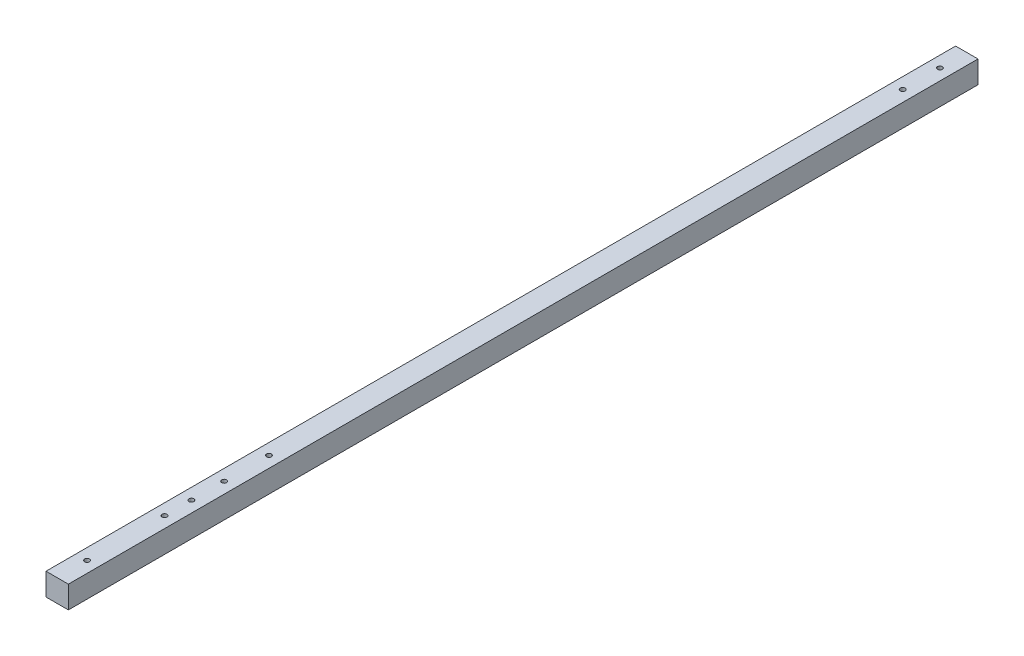
SolidWorks part; units mm, degrees
ref_plane "前视基准面" through (0, 0, 0) normal (0, 0, 1) x (1, 0, 0)
ref_plane "上视基准面" through (0, 0, 0) normal (0, 1, 0) x (1, 0, 0)
ref_plane "右视基准面" through (0, 0, 0) normal (1, 0, 0) x (0, 0, -1)
sketch "草图1" plane through (0, 0, 0) normal (0, 0, 1) x (1, 0, 0)
  line L1 (-7.5, -7.5) -> (7.5, -7.5)
  line L2 (-7.5, -7.5) -> (-7.5, 7.5)
  line L3 (-7.5, 7.5) -> (7.5, 7.5)
  line L4 (7.5, -7.5) -> (7.5, 7.5)
  line L5 (-7.5, -7.5) -> (7.5, 7.5) construction
  line L6 (-7.5, 7.5) -> (7.5, -7.5) construction
  point P0 (0, 0)
  dimension "D1" = 15
  dimension "D2" = 15
extrude "凸台-拉伸1" add sketch "草图1" along normal blind 610
sketch "草图2" plane through (0, 7.5, 0) normal (0, 1, 0) x (1, 0, 0)
  line L0 (7.5, -610) -> (-7.5, -610) construction
  line L1 (7.5, 0) -> (-7.5, 0) construction
  line L2 (0, 0) -> (0, -610) construction
  circle A0 centre (0, -590) radius 1.65
  circle A1 centre (0, -520) radius 1.65
  circle A2 centre (0, -18) radius 1.65
  circle A3 centre (0, -43) radius 1.65
  circle A4 centre (0, -498) radius 1.65
  circle A5 centre (0, -538) radius 1.65
  circle A6 centre (0, -468) radius 1.65
  dimension "D1" = 3.3
  dimension "D3" = 3.3
  dimension "D5" = 3.3
  dimension "D6" = 3.3
  dimension "D9" = 112
  dimension "D10" = 72
  dimension "D11" = 3.3
  dimension "D12" = 3.3
  dimension "D14" = 3.3
  dimension "D2" = 20
  dimension "D4" = 90
  dimension "D7" = 18
  dimension "D8" = 43
  dimension "D13" = 142
extrude "切除-拉伸1" cut sketch "草图2" against normal blind 20
